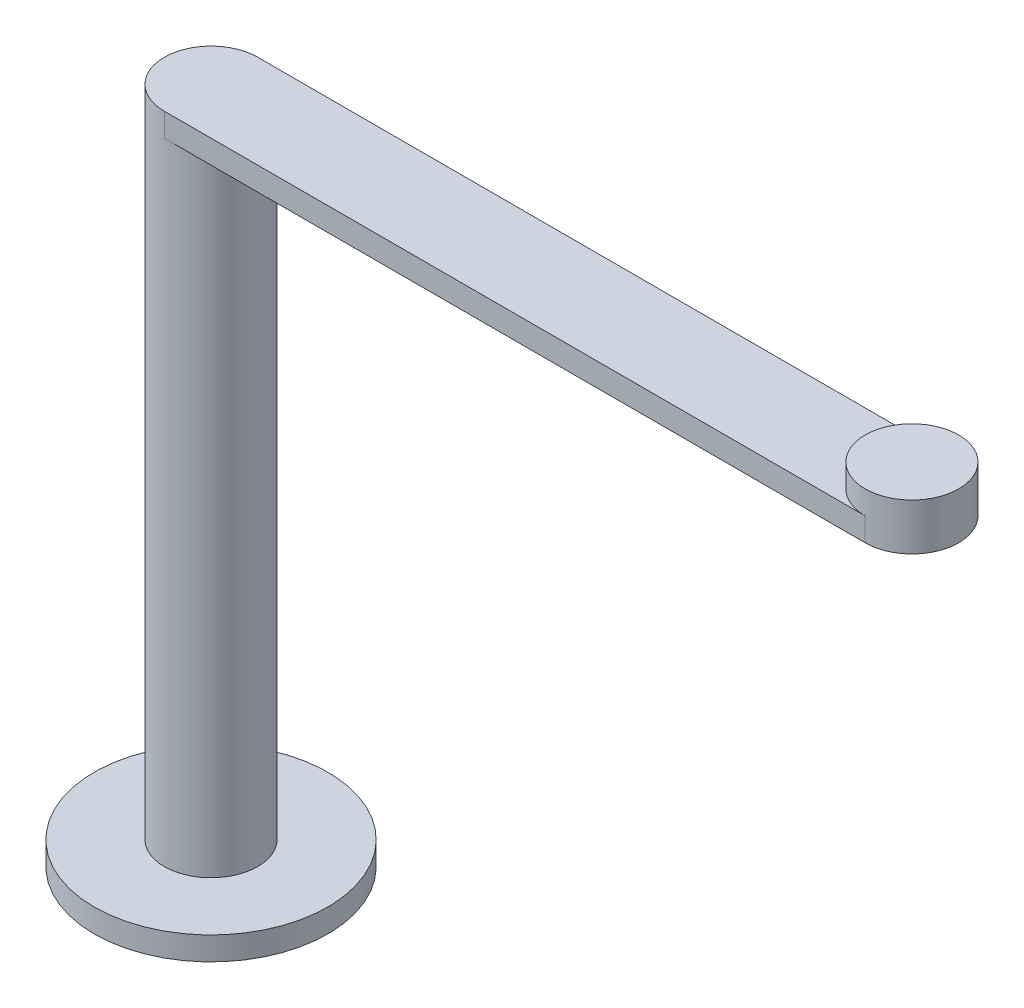
SolidWorks part; units mm, degrees
ref_plane "Front Plane" through (0, 0, 0) normal (0, 0, 1) x (1, 0, 0)
ref_plane "Top Plane" through (0, 0, 0) normal (0, 1, 0) x (1, 0, 0)
ref_plane "Right Plane" through (0, 0, 0) normal (1, 0, 0) x (0, 0, -1)
sketch "Sketch1" plane through (0, 0, 0) normal (0, 1, 0) x (1, 0, 0)
  circle A0 centre (0, 0) radius 50
extrude "Boss-Extrude1" add sketch "Sketch1" along normal blind 10
sketch "Sketch2" plane through (0, 10, 0) normal (0, 1, 0) x (1, 0, 0)
  circle A0 centre (0, 0) radius 20
extrude "Boss-Extrude2" add sketch "Sketch2" along normal blind 280
sketch "Sketch4" plane through (0, 290, 0) normal (0, 1, 0) x (1, 0, 0)
  line L5 (0, 20) -> (300, 20)
  line L6 (0, -20) -> (300, -20)
  line L7 (300, 20) -> (300, -20)
  arc A0 (0, 20) -> (0, -20) centre (0, 0) ccw
  dimension "D1" = 300
extrude "Boss-Extrude3" add sketch "Sketch4" against normal blind 10
sketch "Sketch5" plane through (0, 290, 0) normal (0, 1, 0) x (1, 0, 0)
  line L0 (300, -20) -> (300, 20) construction
  circle A0 centre (300, 0) radius 20
extrude "Boss-Extrude4" add sketch "Sketch5" along normal blind 10 and the other way blind 10
